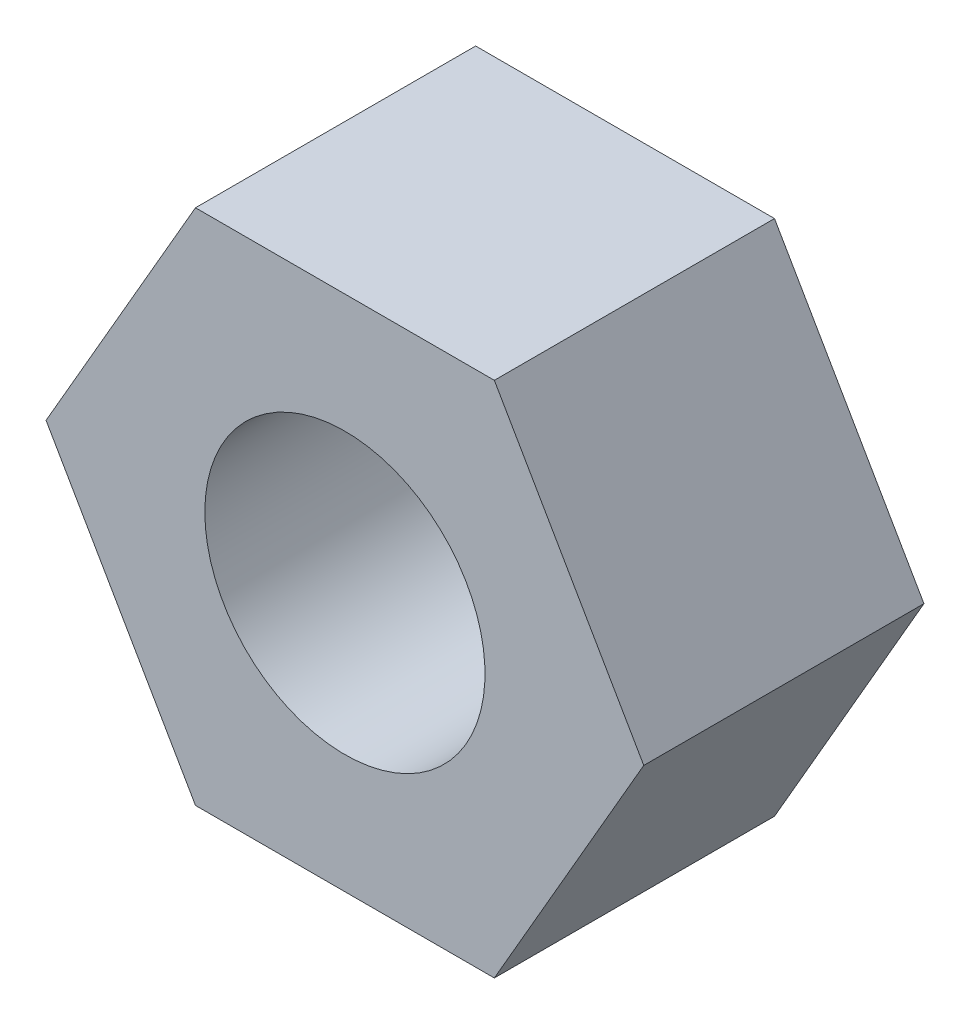
SolidWorks part; units mm, degrees
ref_plane "前视基准面" through (0, 0, 0) normal (0, 0, 1) x (1, 0, 0)
ref_plane "上视基准面" through (0, 0, 0) normal (0, 1, 0) x (1, 0, 0)
ref_plane "右视基准面" through (0, 0, 0) normal (1, 0, 0) x (0, 0, -1)
sketch "草图1" plane through (0, 0, 0) normal (0, 0, 1) x (1, 0, 0)
  line L1 (1.6, 2.7713) -> (-1.6, 2.7713)
  line L2 (-1.6, 2.7713) -> (-3.2, 0)
  line L3 (-3.2, 0) -> (-1.6, -2.7713)
  line L4 (-1.6, -2.7713) -> (1.6, -2.7713)
  line L5 (1.6, -2.7713) -> (3.2, 0)
  line L6 (3.2, 0) -> (1.6, 2.7713)
  circle A0 centre (0, 0) radius 2.7713 construction
  circle A1 centre (0, 0) radius 1.5
  dimension "D2" = 3
  dimension "D1" = 3.2
extrude "凸台-拉伸1" add sketch "草图1" along normal blind 3 contours L1 L2 L3 L4 L5 L6
sketch "草图2" plane through (0, 0, 0) normal (0, 0, -1) x (-1, 0, 0)
  circle A0 centre (0, 0) radius 1.5
  dimension "D1" = 3
extrude "切除-拉伸1" cut sketch "草图2" against normal blind 3
